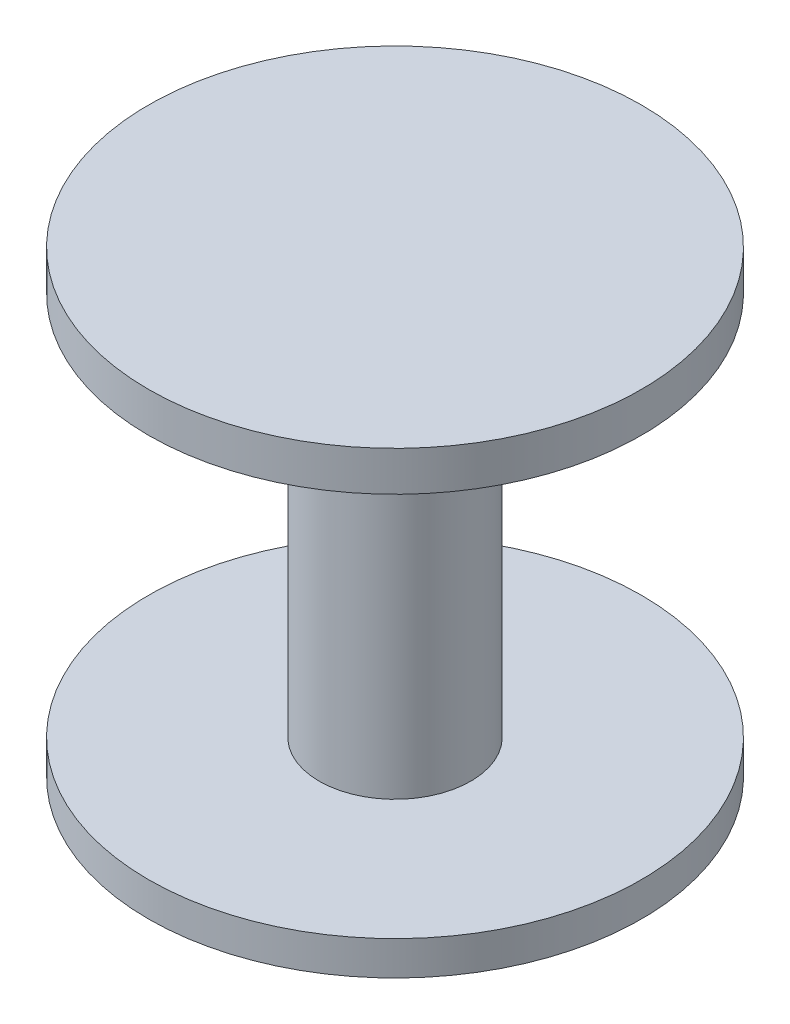
SolidWorks part; units mm, degrees
material "铜"
ref_plane "前视基准面" through (0, 0, 0) normal (0, 0, 1) x (1, 0, 0)
ref_plane "上视基准面" through (0, 0, 0) normal (0, 1, 0) x (1, 0, 0)
ref_plane "右视基准面" through (0, 0, 0) normal (1, 0, 0) x (0, 0, -1)
sketch "草图1" plane through (0, 0, 0) normal (0, 1, 0) x (1, 0, 0)
  circle A0 centre (0, 0) radius 6.5
  dimension "D1" = 13
extrude "凸台-拉伸1" add sketch "草图1" along normal blind 0.9
sketch "草图2" plane through (0, 0.9, 0) normal (0, 1, 0) x (1, 0, 0)
  circle A0 centre (0, 0) radius 2
  dimension "D1" = 4
extrude "凸台-拉伸2" add sketch "草图2" along normal blind 10.15
sketch "草图3" plane through (0, 11.05, 0) normal (0, 1, 0) x (1, 0, 0)
  circle A0 centre (0, 0) radius 6.5
  dimension "D1" = 13
extrude "凸台-拉伸3" add sketch "草图3" along normal blind 1.05
hole_wizard "M2x0.4 螺纹孔1" positions "3D草图2" profile "草图6" tap size "M2x0.4" standard "ANSI Metric"
sketch3d "3D草图2"
  point P3 (0, 0, 0)
sketch "草图6" plane through (0, 0, 0) normal (1, 0, 0) x (0, 0, -1)
  line L0 (0, 0) -> (0, 5.6807)
  line L1 (0, 5.6807) -> (0.8, 5.2)
  line L2 (0.8, 5.2) -> (0.8, 0)
  line L5 (0.8, 0) -> (0, 0)
  line L10 (0, 5.6807) -> (-0.8, 5.2) construction
  line L11 (0, -6.35) -> (0, 107.95) construction
  dimension "螺纹孔钻头直径" = 1.6
  dimension "螺纹孔钻头深度" = 5.2
  dimension "导头角度" = 118
cosmetic thread "孔螺蚊线1" parameters "D1"=4, "D2"=2
